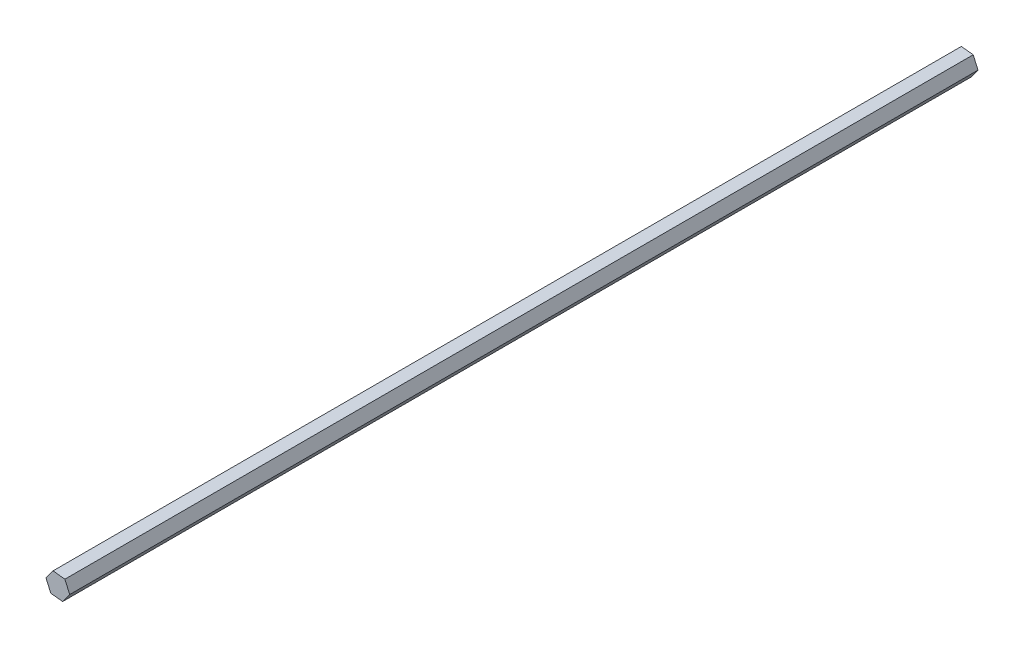
SolidWorks part; units mm, degrees
material "ABS"
ref_plane "Front Plane" through (0, 0, 0) normal (0, 0, 1) x (1, 0, 0)
ref_plane "Top Plane" through (0, 0, 0) normal (0, 1, 0) x (1, 0, 0)
ref_plane "Right Plane" through (0, 0, 0) normal (1, 0, 0) x (0, 0, -1)
sketch "Sketch1" plane through (0, 0, 0) normal (0, 0, 1) x (1, 0, 0)
  line L1 (4.3343, 5.9141) -> (-2.9546, 6.7107)
  line L2 (-2.9546, 6.7107) -> (-7.2889, 0.7966)
  line L3 (-7.2889, 0.7966) -> (-4.3343, -5.9141)
  line L4 (-4.3343, -5.9141) -> (2.9546, -6.7107)
  line L5 (2.9546, -6.7107) -> (7.2889, -0.7966)
  line L6 (7.2889, -0.7966) -> (4.3343, 5.9141)
  circle A0 centre (0, 0) radius 6.35 construction
  dimension "D1" = 12.7
extrude "Boss-Extrude1" add sketch "Sketch1" along normal blind 558.8
